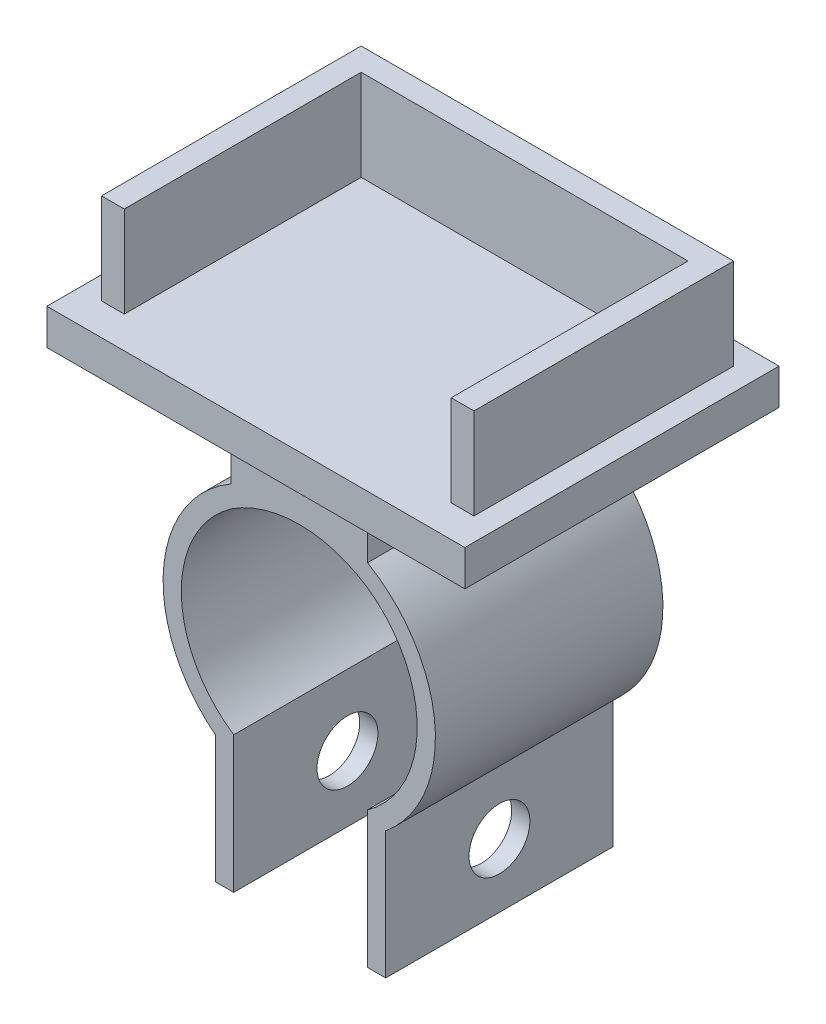
SolidWorks part; units mm, degrees
ref_plane "Front Plane" through (0, 0, 0) normal (0, 0, 1) x (1, 0, 0)
ref_plane "Top Plane" through (0, 0, 0) normal (0, 1, 0) x (1, 0, 0)
ref_plane "Right Plane" through (0, 0, 0) normal (1, 0, 0) x (0, 0, -1)
sketch "Sketch1" plane through (0, 0, 0) normal (0, 1, 0) x (1, 0, 0)
  line L1 (0, 0) -> (23.33, 0)
  line L2 (0, 0) -> (0, 17.54)
  line L3 (0, 17.54) -> (23.33, 17.54)
  line L4 (23.33, 0) -> (23.33, 17.54)
  dimension "D1" = 23.33
  dimension "D2" = 17.54
extrude "Boss-Extrude1" add sketch "Sketch1" along normal blind 2 contours L2 L3 L4 L1
sketch "Sketch2" plane through (0, 2, 0) normal (0, 1, 0) x (1, 0, 0)
  line L0 (1.27, 1.778) -> (1.27, 16.27)
  line L1 (0, 0) -> (23.33, 0) construction
  line L2 (0, 17.54) -> (23.33, 17.54) construction
  line L3 (0, 0) -> (0, 17.54) construction
  line L4 (22.06, 16.27) -> (22.06, 1.778)
  line L5 (22.06, 16.27) -> (1.27, 16.27)
  line L6 (23.33, 0) -> (23.33, 17.54) construction
  line L7 (2.54, 1.778) -> (2.54, 15)
  line L8 (20.79, 15) -> (2.54, 15)
  line L9 (20.79, 15) -> (20.79, 1.778)
  line L12 (1.27, 1.778) -> (2.54, 1.778)
  line L13 (2.54, 0) -> (2.54, 15) construction
  line L14 (1.27, 0) -> (1.27, 16.27) construction
  line L15 (20.79, 15) -> (20.79, 0) construction
  line L16 (22.06, 16.27) -> (22.06, 0) construction
  line L17 (20.79, 1.778) -> (22.06, 1.778)
  dimension "D1" = 1.27
  dimension "D2" = 1.27
  dimension "D3" = 1.27
  dimension "D5" = 1.778
  dimension "D4" = 1.27
extrude "Boss-Extrude2" add sketch "Sketch2" along normal blind 5.08
sketch "Sketch3" plane through (0, 0, 0) normal (0, -1, 0) x (1, 0, 0)
  line L0 (0, -8.77) -> (23.33, -8.77) construction
  line L1 (7.855, -2.42) -> (15.475, -2.42)
  line L2 (7.855, -2.42) -> (7.855, -15.12)
  line L3 (7.855, -15.12) -> (15.475, -15.12)
  line L4 (15.475, -2.42) -> (15.475, -15.12)
  line L5 (0, 0) -> (0, -17.54) construction
  line L6 (23.33, 0) -> (23.33, -17.54) construction
  line L7 (11.665, 0) -> (11.665, -17.54) construction
  line L8 (0, 0) -> (23.33, 0) construction
  line L9 (0, -17.54) -> (23.33, -17.54) construction
  point P10 (15.475, -8.77)
  point P17 (11.665, -15.12)
  dimension "D1" = 0
  dimension "D2" = 0
  dimension "D3" = 7.62
  dimension "D4" = 12.7
extrude "Boss-Extrude3" add sketch "Sketch3" along normal blind 5.08
sketch "Sketch4" plane through (0, 0, -2.42) normal (0, 0, 1) x (1, 0, 0)
  circle A0 centre (11.665, -10.7823) radius 6.858
extrude "Cut-Extrude2" cut sketch "Sketch4" against normal through all contours A0
sketch "Sketch5" plane through (0, 0, -2.42) normal (0, 0, 1) x (1, 0, 0)
  line L0 (15.475, -15.8206) -> (15.475, -17.0269)
  line L1 (8.0069, -15.9252) -> (8.0069, -17.1126)
  line L4 (15.475, -15.8206) -> (15.475, -23.4406)
  line L5 (15.475, -23.4406) -> (16.491, -23.4406)
  line L6 (16.491, -16.3221) -> (16.491, -23.4406)
  line L8 (8.0069, -15.9252) -> (8.0069, -23.5452)
  line L9 (8.0069, -23.5452) -> (6.9909, -23.5452)
  line L10 (6.9909, -16.4437) -> (6.9909, -23.5452)
  arc A0 (15.475, -15.8206) -> (8.0069, -15.9252) centre (11.665, -10.4503) ccw
  arc A1 (16.491, -16.3221) -> (6.9909, -16.4437) centre (11.665, -10.4503) ccw
  circle A2 centre (11.665, -10.4503) radius 6.5845 construction
  circle A3 centre (11.665, -10.4503) radius 7.6005 construction
  line M9 (7.855, 0) -> (7.855, -5.08)
  line M11 (15.475, -5.08) -> (15.475, 0)
  dimension "D2" = 1.016
  dimension "D3" = 1.016
  dimension "D1" = 1.016
extrude "Boss-Extrude4" add sketch "Sketch5" against normal blind 12.7 contours L6 A1 A0 L0 L4 L5 M11 | A1 L10 L9 L8 L1 A0 M9
sketch "Sketch6" plane through (16.491, 0, 0) normal (1, 0, 0) x (0, 0, -1)
  line L0 (2.42, -19.8813) -> (15.12, -19.8813) construction
  line L1 (2.42, -16.3221) -> (2.42, -23.4406) construction
  line L2 (15.12, -16.3221) -> (15.12, -23.4406) construction
  line L3 (15.12, -23.4406) -> (2.42, -23.4406) construction
  line L4 (8.77, -23.4406) -> (8.77, -16.3221) construction
  line L5 (15.12, -16.3221) -> (2.42, -16.3221) construction
  circle A0 centre (8.77, -19.8813) radius 1.7
  dimension "D1" = 3.4
extrude "Cut-Extrude3" cut sketch "Sketch6" against normal through all
